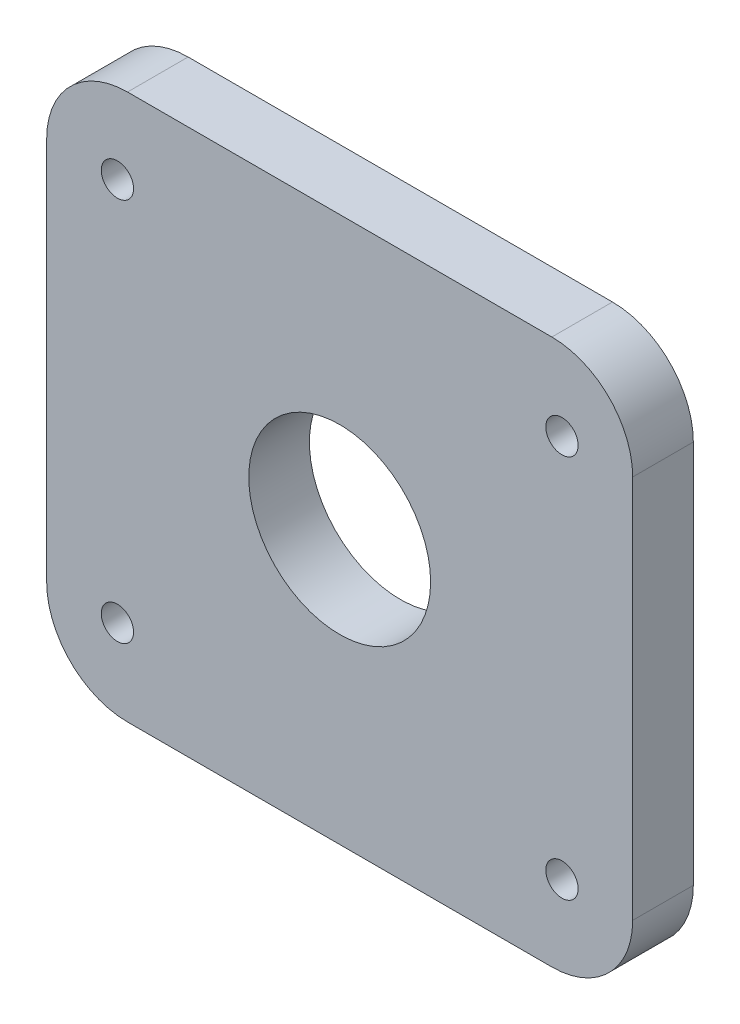
SolidWorks part; units mm, degrees
ref_plane "Спереди" through (0, 0, 0) normal (0, 0, 1) x (1, 0, 0)
ref_plane "Сверху" through (0, 0, 0) normal (0, 1, 0) x (1, 0, 0)
ref_plane "Справа" through (0, 0, 0) normal (1, 0, 0) x (0, 0, -1)
sketch "Эскиз1" plane through (0, 0, 0) normal (0, 0, 1) x (1, 0, 0)
  line L1 (4, 0) -> (25, 0)
  line L2 (0, 4) -> (0, 23)
  line L3 (4, 27) -> (25, 27)
  line L4 (29, 4) -> (29, 23)
  arc A0 (4, 0) -> (0, 4) centre (4, 4) cw
  arc A1 (25, 0) -> (29, 4) centre (25, 4) ccw
  arc A2 (25, 27) -> (29, 23) centre (25, 23) cw
  arc A3 (0, 23) -> (4, 27) centre (4, 23) cw
  point P7 (0, 0)
  point P10 (29, 0)
  point P13 (29, 27)
  point P16 (0, 27)
  dimension "D3" = 4
  dimension "D1" = 29
  dimension "D2" = 27
extrude "Бобышка-Вытянуть1" add sketch "Эскиз1" along normal blind 3
sketch "Эскиз2" plane through (0, 0, 3) normal (0, 0, 1) x (1, 0, 0)
  line L0 (25, 27) -> (4, 27) construction
  line L1 (29, 4) -> (29, 23) construction
  circle A0 centre (14.5, 13.5) radius 4.5
  point P4 (14.5, 27)
  point P7 (29, 13.5)
  dimension "D1" = 9
  dimension "D2" = 0
  dimension "D3" = 0
extrude "Вырез-Вытянуть1" cut sketch "Эскиз2" against normal through all
sketch "Эскиз3" plane through (0, 0, 3) normal (0, 0, 1) x (1, 0, 0)
  circle A0 centre (3.5, 4) radius 0.8
  circle A1 centre (14.5, 13.5) radius 4.5 construction
  circle A2 centre (25.5, 4) radius 0.8
  circle A3 centre (25.5, 23) radius 0.8
  circle A4 centre (3.5, 23) radius 0.8
  dimension "D1" = 1.6
  dimension "D3" = 9.5
  dimension "D2" = 11
  dimension "D4" = 2
  dimension "D5" = 2
extrude "Вырез-Вытянуть2" cut sketch "Эскиз3" against normal through all
